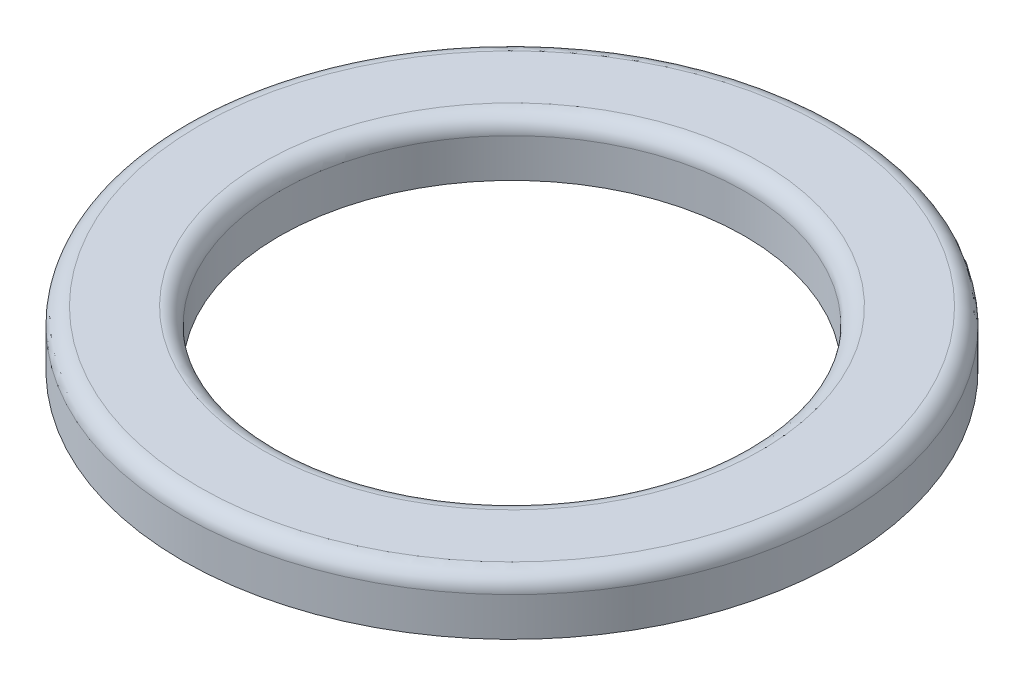
SolidWorks part; units mm, degrees
material "6061-T6 (SS)"
ref_plane "Front Plane" through (0, 0, 0) normal (0, 0, 1) x (1, 0, 0)
ref_plane "Top Plane" through (0, 0, 0) normal (0, 1, 0) x (1, 0, 0)
ref_plane "Right Plane" through (0, 0, 0) normal (1, 0, 0) x (0, 0, -1)
sketch "Sketch1" plane through (0, 0, 0) normal (0, 1, 0) x (1, 0, 0)
  circle A0 centre (0, 0) radius 4.2
  circle A1 centre (0, 0) radius 5.95
  dimension "D1" = 8.4
  dimension "D2" = 11.9
extrude "Boss-Extrude1" add sketch "Sketch1" along normal blind 1
fillet "Fillet1" radius 0.3 2 edges at (0, 1, 5.95) (0, 1, 4.2)
